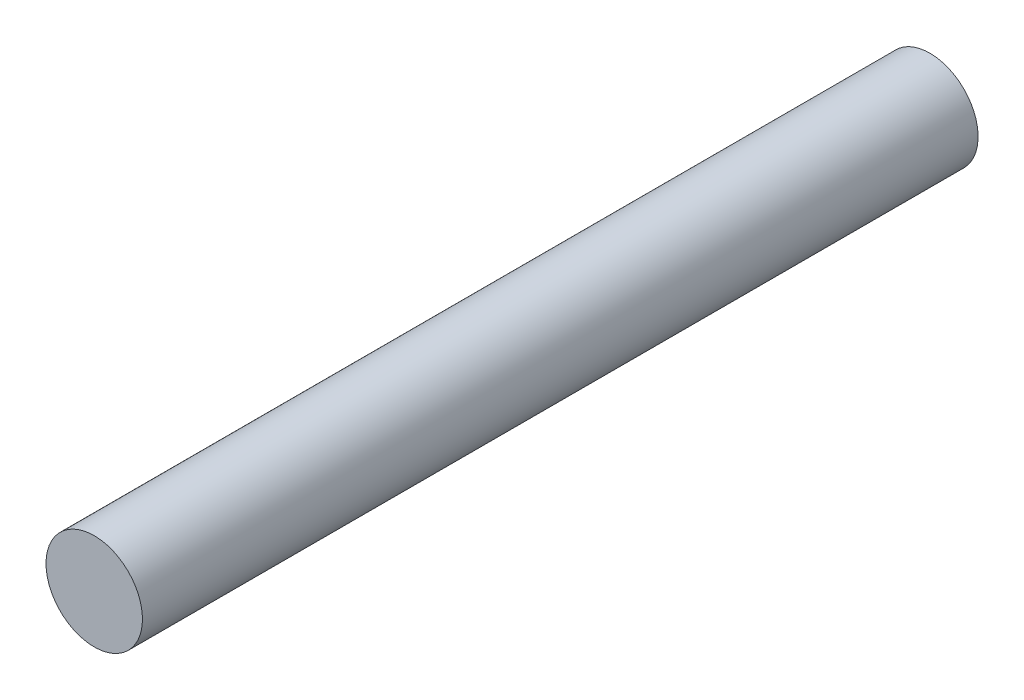
SolidWorks part; units mm, degrees
ref_plane "Front Plane" through (0, 0, 0) normal (0, 0, 1) x (1, 0, 0)
ref_plane "Top Plane" through (0, 0, 0) normal (0, 1, 0) x (1, 0, 0)
ref_plane "Right Plane" through (0, 0, 0) normal (1, 0, 0) x (0, 0, -1)
sketch "Sketch1" plane through (0, 0, 0) normal (0, 0, 1) x (1, 0, 0)
  circle A0 centre (0, 0) radius 1.5
  dimension "D1" = 3
extrude "Boss-Extrude1" add sketch "Sketch1" along normal blind 26
